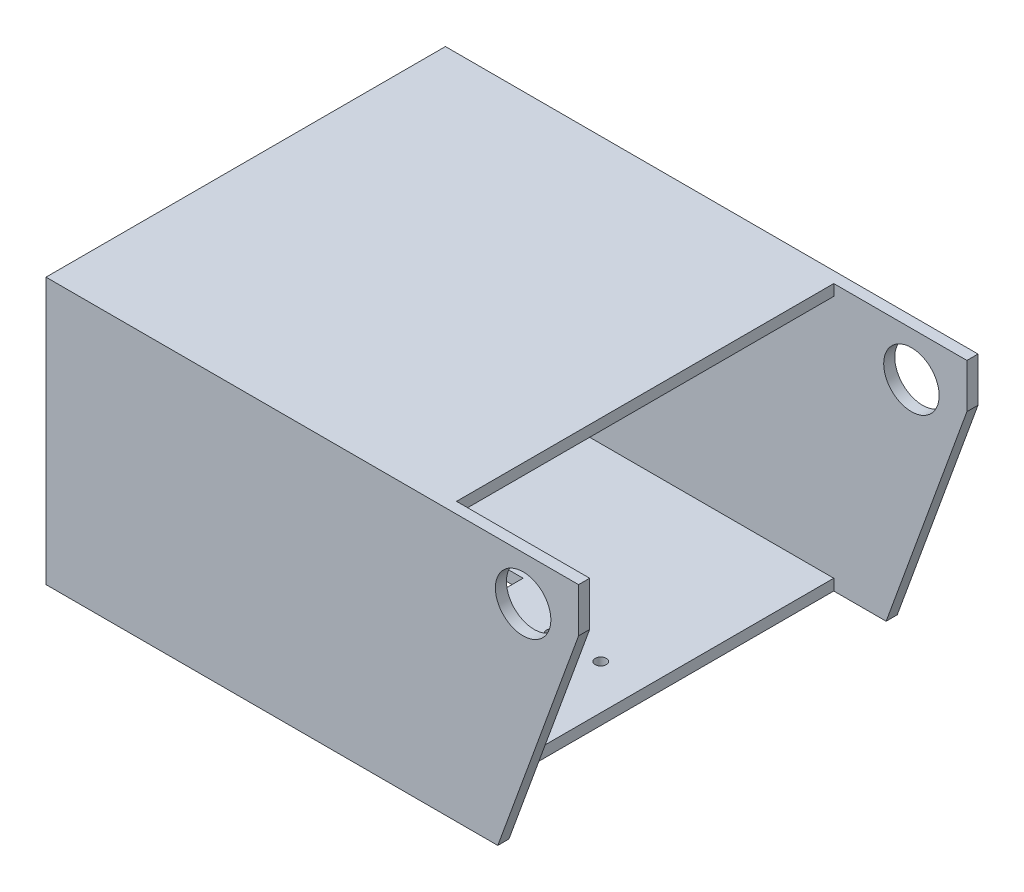
SolidWorks part; units mm, degrees
ref_plane "Front Plane" through (0, 0, 0) normal (0, 0, 1) x (1, 0, 0)
ref_plane "Top Plane" through (0, 0, 0) normal (0, 1, 0) x (1, 0, 0)
ref_plane "Right Plane" through (0, 0, 0) normal (1, 0, 0) x (0, 0, -1)
sketch "Sketch1" plane through (0, 0, 0) normal (0, 1, 0) x (1, 0, 0)
  line L1 (-97.1195, 44.7734) -> (55.2805, 44.7734)
  line L2 (-97.1195, 44.7734) -> (-97.1195, -69.5266)
  line L3 (-97.1195, -69.5266) -> (55.2805, -69.5266)
  line L4 (55.2805, 44.7734) -> (55.2805, -69.5266)
  dimension "D1" = 152.4
  dimension "D2" = 114.3
extrude "Boss-Extrude1" add sketch "Sketch1" along normal blind 76.2
sketch "Sketch3" plane through (0, 0, 0) normal (0, 0, 1) x (1, 0, 0)
  line L0 (55.2805, 76.2) -> (55.2805, 63.5)
  line L1 (55.2805, 76.2) -> (55.2805, 0) construction
  line L2 (55.2805, 63.5) -> (32.1684, 0)
  line L3 (-97.1195, 0) -> (55.2805, 0) construction
  line L4 (32.1684, 0) -> (55.2805, 0)
  line L5 (55.2805, 0) -> (55.2805, 63.5)
  dimension "D1" = 12.7
  dimension "D2" = 20
extrude "Cut-Extrude1" cut sketch "Sketch3" against normal through all and the other way through all contours L2 L4 L5
sketch "Sketch4" plane through (0, 0, 0) normal (0, 0, 1) x (1, 0, 0)
  line L1 (-93.9445, 3.175) -> (28.9934, 3.175)
  line L2 (-93.9445, 3.175) -> (-93.9445, 73.025)
  line L3 (-93.9445, 73.025) -> (28.9934, 73.025)
  line L4 (28.9934, 3.175) -> (28.9934, 73.025)
  line L5 (-97.1195, 0) -> (32.1684, 0) construction
  line L6 (-97.1195, 76.2) -> (-97.1195, 0) construction
  line L8 (-97.1195, 76.2) -> (55.2805, 76.2) construction
  dimension "D1" = 3.175
  dimension "D2" = 3.175
  dimension "D3" = 3.175
  dimension "D4" = 3.175
sketch "Sketch5" plane through (0, 0, 0) normal (0, 1, 0) x (1, 0, 0)
  line L1 (17.1805, 41.5984) -> (55.2805, 41.5984)
  line L2 (17.1805, 41.5984) -> (17.1805, -66.3516)
  line L3 (17.1805, -66.3516) -> (55.2805, -66.3516)
  line L4 (55.2805, 41.5984) -> (55.2805, -66.3516)
  line L5 (55.2805, 44.7734) -> (-97.1195, 44.7734) construction
  line L6 (-97.1195, -69.5266) -> (55.2805, -69.5266) construction
  line L7 (55.2805, -69.5266) -> (55.2805, 44.7734) construction
  dimension "D1" = 3.175
  dimension "D2" = 3.175
  dimension "D3" = 0
  dimension "D4" = 38.1
extrude "Cut-Extrude4" cut sketch "Sketch5" along normal through all contours L3 L4 L1 L2
sketch "Sketch6" plane through (0, 0, 69.5266) normal (0, 0, 1) x (1, 0, 0)
  line L0 (55.2805, 76.2) -> (55.2805, 63.5) construction
  line L1 (-97.1195, 76.2) -> (55.2805, 76.2) construction
  circle A0 centre (39.4055, 63.5) radius 7.9375
  dimension "D1" = 15.875
  dimension "D2" = 15.875
  dimension "D3" = 12.7
extrude "Cut-Extrude5" cut sketch "Sketch6" against normal through all both and the other way through all
sketch "Sketch8" plane through (-97.1195, 0, 0) normal (-1, 0, 0) x (0, 0, 1)
  line L0 (-44.7734, 76.2) -> (-44.7734, 0) construction
  line L1 (-41.5984, 73.025) -> (66.3516, 73.025)
  line L2 (-41.5984, 73.025) -> (-41.5984, 3.175)
  line L3 (-41.5984, 3.175) -> (66.3516, 3.175)
  line L4 (66.3516, 73.025) -> (66.3516, 3.175)
  line L5 (69.5266, 76.2) -> (69.5266, 0) construction
  line L6 (-44.7734, 76.2) -> (69.5266, 76.2) construction
  line L7 (-44.7734, 0) -> (69.5266, 0) construction
  dimension "D1" = 3.175
  dimension "D2" = 3.175
  dimension "D3" = 3.175
  dimension "D4" = 3.175
extrude "Cut-Extrude6" cut sketch "Sketch8" against normal through all
sketch "Sketch9" plane through (0, 0, 0) normal (0, -1, 0) x (1, 0, 0)
  line L0 (17.1805, -41.5984) -> (17.1805, 66.3516) construction
  line L1 (-97.1195, 69.5266) -> (32.1684, 69.5266) construction
  circle A0 centre (4.4805, 12.3766) radius 1.5875
  circle A1 centre (-9.4895, 12.3766) radius 1.5875
  dimension "D1" = 3.175
  dimension "D2" = 3.175
  dimension "D3" = 0
  dimension "D4" = 12.7
  dimension "D5" = 13.97
  dimension "D6" = 57.15
extrude "Cut-Extrude7" cut sketch "Sketch9" against normal blind 3.175
sketch "Sketch10" plane through (0, 0, 0) normal (0, -1, 0) x (1, 0, 0)
  line L0 (-97.1195, 69.5266) -> (32.1684, 69.5266) construction
  line L1 (-90.7695, 21.9016) -> (-27.2695, 21.9016)
  line L2 (-90.7695, 21.9016) -> (-90.7695, 2.8516)
  line L3 (-90.7695, 2.8516) -> (-27.2695, 2.8516)
  line L4 (-27.2695, 21.9016) -> (-27.2695, 2.8516)
  line L5 (-90.7695, 21.9016) -> (-27.2695, 2.8516) construction
  line L6 (-90.7695, 2.8516) -> (-27.2695, 21.9016) construction
  line L7 (-97.1195, -44.7734) -> (-97.1195, 69.5266) construction
  point P0 (-59.0195, 12.3766)
  dimension "D1" = 57.15
  dimension "D2" = 38.1
  dimension "D3" = 63.5
  dimension "D4" = 19.05
extrude "Cut-Extrude8" cut sketch "Sketch10" against normal blind 5.715
